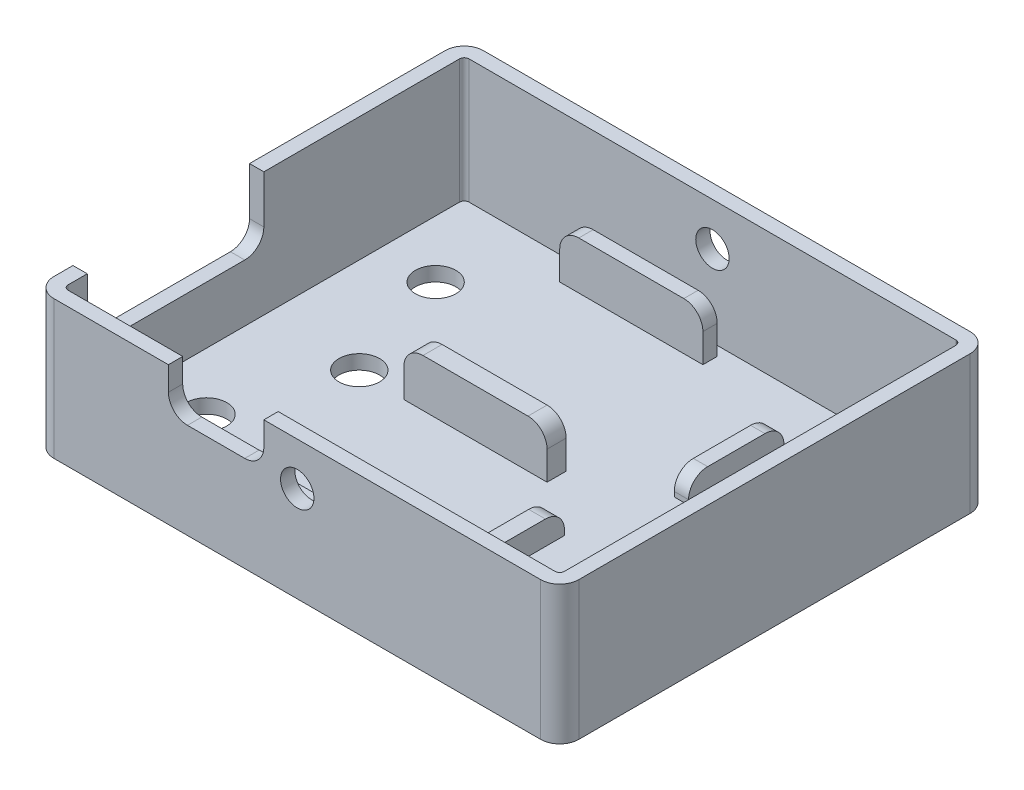
SolidWorks part; units mm, degrees
ref_plane "Front" through (0, 0, 0) normal (0, 0, 1) x (1, 0, 0)
ref_plane "Top" through (0, 0, 0) normal (0, 1, 0) x (1, 0, 0)
ref_plane "Right" through (0, 0, 0) normal (1, 0, 0) x (0, 0, -1)
sketch "Croquis1" plane through (0, 0, 0) normal (0, 1, 0) x (1, 0, 0)
  line L1 (-25.5, -22.5) -> (25.5, -22.5)
  line L2 (-27.5, -20.5) -> (-27.5, 20.5)
  line L3 (-25.5, 22.5) -> (25.5, 22.5)
  line L4 (27.5, -20.5) -> (27.5, 20.5)
  line L5 (-27.5, -22.5) -> (27.5, 22.5) construction
  line L6 (-27.5, 22.5) -> (27.5, -22.5) construction
  arc A0 (-25.5, 22.5) -> (-27.5, 20.5) centre (-25.5, 20.5) ccw
  arc A1 (27.5, 20.5) -> (25.5, 22.5) centre (25.5, 20.5) ccw
  arc A2 (25.5, -22.5) -> (27.5, -20.5) centre (25.5, -20.5) ccw
  arc A3 (-27.5, -20.5) -> (-25.5, -22.5) centre (-25.5, -20.5) ccw
  point P0 (0, 0)
  dimension "D3" = 2
  dimension "D4" = 2
  dimension "D5" = 2
  dimension "D6" = 2
  dimension "D1" = 55
  dimension "D2" = 45
extrude "Saliente-Extruir1" add sketch "Croquis1" along normal blind 1.5
sketch "Croquis3" plane through (0, 1.5, 0) normal (0, 1, 0) x (1, 0, 0)
  line L0 (-27.5, -25.965) -> (-27.5, 25.965) construction
  line L1 (-27.5, 20.5) -> (-27.5, -20.5) construction
  line L2 (-1000, 0) -> (49000, 0) construction
  line L3 (0, -1000) -> (0, 49000) construction
  line L4 (27.5, -25.965) -> (27.5, 25.965) construction
  line L5 (-29.0599, 22.5) -> (31.1111, 22.5) construction
  line L6 (-29.0599, -22.5) -> (31.1111, -22.5) construction
  line L7 (-25.5, 21) -> (25.5, 21)
  line L8 (-25.5, 22.5) -> (25.5, 22.5)
  line L9 (-27.5, 20.5) -> (-27.5, -20.5)
  line L10 (-25.5, -22.5) -> (25.5, -22.5)
  line L11 (27.5, 20.5) -> (27.5, -20.5)
  line L12 (26, 20.5) -> (26, -20.5)
  line L13 (-25.5, -21) -> (25.5, -21)
  line L14 (-26, 20.5) -> (-26, -20.5)
  line L15 (25.5, 22.5) -> (-25.5, 22.5) construction
  arc A0 (-25.5, 22.5) -> (-27.5, 20.5) centre (-25.5, 20.5) ccw
  arc A1 (27.5, 20.5) -> (25.5, 22.5) centre (25.5, 20.5) ccw
  arc A2 (25.5, -22.5) -> (27.5, -20.5) centre (25.5, -20.5) ccw
  arc A3 (-27.5, -20.5) -> (-25.5, -22.5) centre (-25.5, -20.5) ccw
  arc A4 (26, 20.5) -> (25.5, 21) centre (25.5, 20.5) ccw
  arc A5 (25.5, -21) -> (26, -20.5) centre (25.5, -20.5) ccw
  arc A6 (-26, -20.5) -> (-25.5, -21) centre (-25.5, -20.5) ccw
  arc A7 (-25.5, 21) -> (-26, 20.5) centre (-25.5, 20.5) ccw
  point P16 (27.5, 0)
  point P17 (-27.5, 0)
  point P23 (-27.5, 22.5)
  point P28 (27.5, -22.5)
  dimension "D1" = 2
  dimension "D2" = 2
  dimension "D3" = 2
  dimension "D4" = 2
  dimension "D6" = 1.5
  dimension "D5" = 1.5
extrude "Saliente-Extruir3" add sketch "Croquis3" along normal blind 13
sketch "Croquis4" plane through (0, 1.5, 0) normal (0, 1, 0) x (1, 0, 0)
  line L0 (25.5, 21) -> (-25.5, 21) construction
  line L1 (-13.5, 20) -> (1.5, 20)
  line L2 (-13.5, 20) -> (-13.5, 18.5)
  line L3 (-13.5, 18.5) -> (1.5, 18.5)
  line L4 (1.5, 20) -> (1.5, 18.5)
  line L5 (-26, 20.5) -> (-26, -20.5) construction
  line L6 (-1000, 0) -> (49000, 0) construction
  line L7 (0, -1000) -> (0, 49000) construction
  line L8 (1.5, -20) -> (1.5, -18.5)
  line L9 (-13.5, -18.5) -> (1.5, -18.5)
  line L10 (-13.5, -20) -> (1.5, -20)
  line L11 (-13.5, -20) -> (-13.5, -18.5)
  line L12 (-3.5, -984.5) -> (-3.5, 49015.5) construction
  line L13 (-13.5, 18.5) -> (1.5, 20) construction
  line L14 (1.5, 18.5) -> (-13.5, 20) construction
  line L15 (4, 1.675) -> (4, -0.325)
  line L16 (-11, -0.325) -> (4, 1.675) construction
  line L17 (-11, -0.325) -> (4, -0.325)
  line L18 (-11, 1.675) -> (-11, -0.325)
  line L19 (-11, 1.675) -> (4, 1.675)
  line L20 (4, -0.325) -> (-11, 1.675) construction
  dimension "D1" = 15
  dimension "D2" = 1.5
  dimension "D3" = 1
  dimension "D4" = 12.5
  dimension "D5" = 16.825
  dimension "D6" = 2
  dimension "D8" = 15
extrude "Saliente-Extruir4" add sketch "Croquis4" along normal blind 5
sketch "Croquis5" plane through (0, 1.5, 0) normal (0, 1, 0) x (1, 0, 0)
  line L0 (-1000, 0) -> (49000, 0) construction
  line L1 (0, -1000) -> (0, 49000) construction
  line L2 (-26, 20.5) -> (-26, -20.5) construction
  line L3 (12, 5) -> (13.5, 5)
  line L4 (12, 5) -> (12, 15)
  line L5 (12, 15) -> (13.5, 15)
  line L6 (13.5, 5) -> (13.5, 15)
  line L7 (12, 5) -> (13.5, 15) construction
  line L8 (12, 15) -> (13.5, 5) construction
  line L9 (-13.5, 18.5) -> (1.5, 18.5) construction
  line L11 (12.75, -990) -> (12.75, 49010) construction
  line L12 (8, -14.25) -> (9.75, -14.25)
  line L13 (9.75, -14.25) -> (9.75, -4.25)
  line L14 (8, -14.25) -> (9.75, -4.25) construction
  line L15 (8, -4.25) -> (9.75, -14.25) construction
  line L16 (8, -4.25) -> (9.75, -4.25)
  line L17 (8, -14.25) -> (8, -4.25)
  point P4 (12.75, 10)
  dimension "D1" = 10
  dimension "D2" = 1.5
  dimension "D3" = 38
  dimension "D4" = 3.5
  dimension "D5" = 10
  dimension "D6" = 1.75
  dimension "D7" = 34
  dimension "D8" = 4.25
  dimension "D9" = 1.75
extrude "Saliente-Extruir5" add sketch "Croquis5" along normal blind 2.5
sketch "Croquis6" plane through (-27.5, 0, 0) normal (-1, 0, 0) x (0, 0, 1)
  line L0 (-20.5, 14.5) -> (20.5, 14.5) construction
  line L1 (18.5, 14.5) -> (0, 14.5)
  line L2 (18.5, 14.5) -> (18.5, 7.5)
  line L3 (18.5, 7.5) -> (0, 7.5)
  line L4 (0, 14.5) -> (0, 7.5)
  line L5 (20.5, 14.5) -> (20.5, 0) construction
  dimension "D1" = 18.5
  dimension "D2" = 2
  dimension "D3" = 7
extrude "Cortar-Extruir1" cut sketch "Croquis6" against normal up to surface (1.5 mm away) up to face at (-26, 8, 0)
sketch "Croquis7" plane through (0, 0, 22.5) normal (0, 0, 1) x (1, 0, 0)
  line L0 (-25.5, 14.5) -> (25.5, 14.5) construction
  line L1 (-13.5, 14.5) -> (-3.5, 14.5)
  line L2 (-13.5, 14.5) -> (-13.5, 10)
  line L3 (-13.5, 10) -> (-3.5, 10)
  line L4 (-3.5, 14.5) -> (-3.5, 10)
  line L5 (-25.5, 14.5) -> (-25.5, 0) construction
  dimension "D1" = 10
  dimension "D2" = 4.5
  dimension "D3" = 12
extrude "Cortar-Extruir2" cut sketch "Croquis7" against normal up to surface (1.5 mm away) up to face at (0, 8, 21)
sketch "Croquis8" plane through (0, 1.5, 0) normal (0, 1, 0) x (1, 0, 0)
  line L0 (23, -1018) -> (23, 48982) construction
  line L1 (-977, -18) -> (49023, -18) construction
  line L2 (26, -20.5) -> (26, 20.5) construction
  line L3 (-25.5, -21) -> (25.5, -21) construction
  line L4 (-976.5, -0.5) -> (49023.5, -0.5) construction
  line L5 (26, -20.5) -> (26, 20.5) construction
  circle A0 centre (23, -18) radius 2.25
  circle A1 centre (23, -18) radius 1.5
  circle A2 centre (23, -0.5) radius 2.25
  circle A3 centre (23, -0.5) radius 1.5
  dimension "D1" = 4.5
  dimension "D2" = 3
  dimension "D3" = 3
  dimension "D4" = 3
  dimension "D5" = 0.75
  dimension "D6" = 3
  dimension "D7" = 17.5
  dimension "D8" = 3
extrude "Saliente-Extruir6" add sketch "Croquis8" along normal blind 2.25
sketch "Croquis9" plane through (0, 0, -22.5) normal (0, 0, -1) x (-1, 0, 0)
  line L0 (0, -1000) -> (0, 49000) construction
  line L1 (-1000, 10) -> (49000, 10) construction
  line L2 (-25.5, 14.5) -> (25.5, 14.5) construction
  circle A0 centre (0, 10) radius 1.75
  dimension "D2" = 3.5
  dimension "D1" = 4.5
extrude "Cortar-Extruir3" cut sketch "Croquis9" against normal up to surface (45 mm away) up to face at (-4.25, 9.75, 22.5)
sketch "Croquis10" plane through (0, 1.5, 0) normal (0, 1, 0) x (1, 0, 0)
  line L0 (-1000, 0) -> (49000, 0) construction
  line L1 (0, -1000) -> (0, 49000) construction
  line L2 (-26, 0) -> (-26, -18.5) construction
  circle A0 centre (-16, 0) radius 2.125
  circle A1 centre (16, 0) radius 2.125
  dimension "D1" = 4.25
  dimension "D2" = 10
extrude "Cortar-Extruir4" cut sketch "Croquis10" against normal up to surface (1.5 mm away) up to face at (0, 0, 0)
sketch "Croquis11" plane through (0, 1.5, 0) normal (0, 1, 0) x (1, 0, 0)
  line L0 (-1000, 0) -> (49000, 0) construction
  line L1 (0, -1000) -> (0, 49000) construction
  circle A0 centre (-20, 12) radius 2.125
  circle A1 centre (20, 12) radius 2.125
  circle A2 centre (20, -12) radius 2.125
  circle A3 centre (-20, -12) radius 2.125
  dimension "D2" = 4.25
  dimension "D3" = 12
  dimension "D1" = 20
extrude "Cortar-Extruir5" cut sketch "Croquis11" against normal up to surface (1.5 mm away) up to face at (16, 0, 2.125)
sketch "Croquis12" plane through (-27.5, 0, 0) normal (-1, 0, 0) x (0, 0, 1)
  line L0 (9.25, -993.5) -> (9.25, 49006.5) construction
  line L1 (0, 7.5) -> (18.5, 7.5) construction
  line L2 (0, 7.5) -> (2, 7.5)
  line L3 (0, 9.5) -> (0, 7.5)
  line L8 (18.5, 9.5) -> (18.5, 7.5)
  line L9 (18.5, 7.5) -> (16.5, 7.5)
  arc A0 (16.5, 7.5) -> (18.5, 9.5) centre (16.5, 9.5) ccw
  arc A1 (2, 7.5) -> (0, 9.5) centre (2, 9.5) cw
  point P5 (9.25, 7.5)
  dimension "D1" = 2
extrude "Saliente-Extruir8" add sketch "Croquis12" against normal blind 1.5
sketch "Croquis13" plane through (0, 0, 22.5) normal (0, 0, 1) x (1, 0, 0)
  line L0 (-8.5, -991) -> (-8.5, 49009) construction
  line L1 (-13.5, 10) -> (-3.5, 10) construction
  line L2 (-13.5, 12) -> (-13.5, 10)
  line L7 (-13.5, 10) -> (-11.5, 10)
  line L8 (-3.5, 12) -> (-3.5, 10)
  line L9 (-3.5, 10) -> (-5.5, 10)
  arc A0 (-3.5, 12) -> (-5.5, 10) centre (-5.5, 12) cw
  arc A1 (-11.5, 10) -> (-13.5, 12) centre (-11.5, 12) cw
  point P5 (-8.5, 10)
  point P14 (-13.5, 10)
  dimension "D1" = 2
extrude "Saliente-Extruir9" add sketch "Croquis13" against normal blind 1.5
fillet "Redondeo2" radius 2 10 edges at (-13.5, 6.5, 19.25) (1.5, 6.5, 19.25) (12.75, 4, -5) (12.75, 4, -15) (8.875, 4, 4.25) (8.875, 4, 14.25) (-11, 6.5, -0.675) (4, 6.5, -0.675) (1.5, 6.5, -19.25) (-13.5, 6.5, -19.25)
